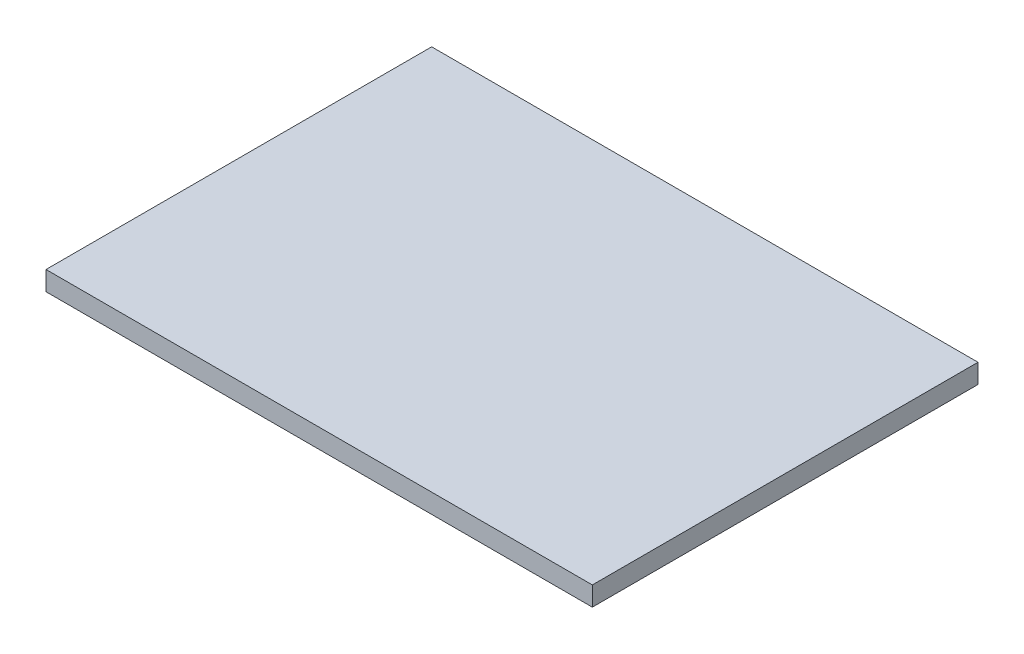
SolidWorks part; units mm, degrees
material "Polyurethane Foam Rigid"
ref_plane "Front Plane" through (0, 0, 0) normal (0, 0, 1) x (1, 0, 0)
ref_plane "Top Plane" through (0, 0, 0) normal (0, 1, 0) x (1, 0, 0)
ref_plane "Right Plane" through (0, 0, 0) normal (1, 0, 0) x (0, 0, -1)
sketch "Sketch1" plane through (0, 0, 0) normal (0, 1, 0) x (1, 0, 0)
  line L1 (0, 0) -> (170, 0)
  line L2 (0, 0) -> (0, 120)
  line L3 (0, 120) -> (170, 120)
  line L4 (170, 0) -> (170, 120)
  dimension "D1" = 120
  dimension "D2" = 170
extrude "Boss-Extrude1" add sketch "Sketch1" along normal blind 6
